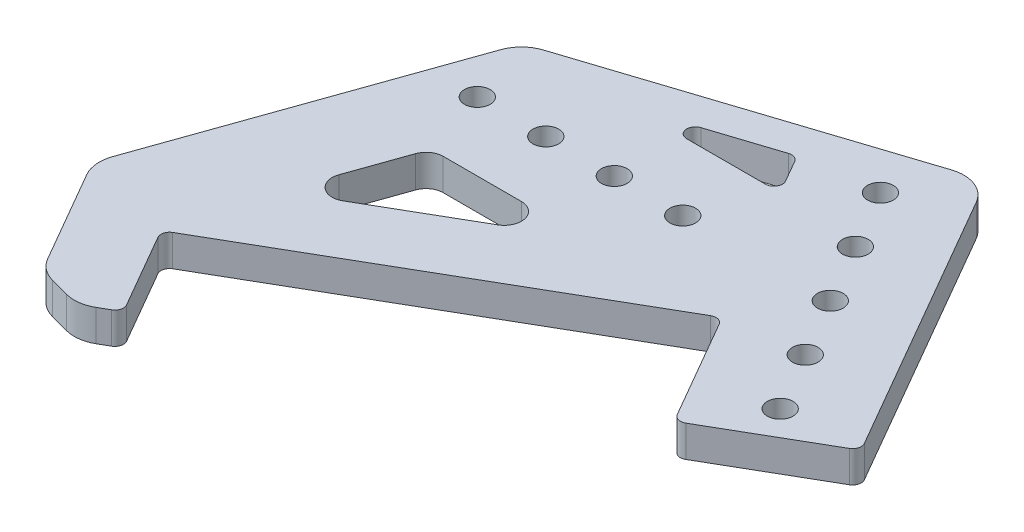
SolidWorks part; units mm, degrees
ref_plane "Front Plane" through (0, 0, 0) normal (0, 0, 1) x (1, 0, 0)
ref_plane "Top Plane" through (0, 0, 0) normal (0, 1, 0) x (1, 0, 0)
ref_plane "Right Plane" through (0, 0, 0) normal (1, 0, 0) x (0, 0, -1)
sketch "Sketch1" plane through (0, 0, 0) normal (0, 1, 0) x (1, 0, 0)
  line L0 (0, 0) -> (-31.75, 54.9926) construction
  line L1 (-15.875, 27.4963) -> (-85.725, 27.4963) construction
  line L2 (-10.9985, -6.35) -> (-23.2073, 14.7963)
  line L3 (-10.9985, -6.35) -> (10.9985, 6.35)
  line L4 (-23.2073, 14.7963) -> (-89.1985, -23.3037)
  line L5 (10.9985, 6.35) -> (-20.7515, 61.3426)
  line L6 (-10.9985, -6.35) -> (-20.7515, 61.3426) construction
  line L7 (-42.7485, 48.6426) -> (10.9985, 6.35) construction
  line L8 (-37.872, 40.1963) -> (-42.1959, 47.6855)
  line L9 (-65.2068, 40.1963) -> (-37.872, 40.1963)
  line L12 (-85.725, 40.1963) -> (-20.7515, 61.3426)
  line L13 (-65.2068, 40.1963) -> (-42.1959, 47.6855)
  line L14 (-89.1985, -23.3037) -> (-82.8485, -34.3022)
  line L16 (-83.7598, 34.1581) -> (-18.7863, 55.3044) construction
  line L17 (-106.547, -18.6552) -> (-93.847, -40.6522)
  line L18 (-106.547, -18.6552) -> (-85.725, 40.1963)
  line L19 (-29.5573, 25.7948) -> (-106.547, -18.6552) construction
  line L20 (-82.8485, -34.3022) -> (-79.6735, -39.8015)
  line L21 (-79.6735, -39.8015) -> (-85.1727, -42.9765)
  line L22 (-85.1727, -42.9765) -> (-93.847, -40.6522)
  circle A0 centre (-28.575, 49.4934) radius 2.3813
  circle A1 centre (-22.225, 38.4948) radius 2.3813
  circle A2 centre (-15.875, 27.4963) radius 2.3813
  circle A3 centre (-9.525, 16.4978) radius 2.3813
  circle A4 centre (-3.175, 5.4993) radius 2.3813
  circle A5 centre (-43.2397, 27.4963) radius 2.3812
  circle A6 centre (-55.9397, 27.4963) radius 2.3813
  circle A7 centre (-68.6397, 27.4963) radius 2.3813
  circle A8 centre (-81.3397, 27.4963) radius 2.3812
  point P30 (-85.725, 27.4963)
  dimension "D3" = 4.7625
  dimension "D6" = 4.7625
  dimension "D1" = 63.5
  dimension "D2" = 69.85
  dimension "D4" = 6.35
  dimension "D7" = 27.3647
  dimension "D9" = 25.4
  dimension "D10" = 60
  dimension "D12" = 6.35
  dimension "D13" = 76.2
  dimension "D14" = 12.7
  dimension "D16" = 19.05
  dimension "D17" = 6.35
  dimension "D15" = 12.7
  dimension "D5" = 5
  dimension "D8" = 4
extrude "Boss-Extrude1" add sketch "Sketch1" along normal blind 5.842
fillet "Fillet1" radius 1.5875 3 edges at (-37.872, 2.921, -40.1963) (-65.2068, 2.921, -40.1963) (-42.1959, 2.921, -47.6855)
fillet "Fillet2" radius 6.35 5 edges at (-85.725, 2.921, -40.1963) (-20.7515, 2.921, -61.3426) (-85.1727, 2.921, 42.9765) (-93.847, 2.921, 40.6522) (-106.547, 2.921, 18.6552)
fillet "Fillet3" radius 1.5875 5 edges at (-79.6735, 2.921, 39.8015) (-89.1985, 2.921, 23.3037) (-23.2073, 2.921, -14.7963) (10.9985, 2.921, -6.35) (-10.9985, 2.921, 6.35)
sketch "Sketch2" plane through (0, 5.842, 0) normal (0, 1, 0) x (1, 0, 0)
  line L0 (-84.55, -5.9552) -> (-48.6073, 14.7963)
  line L1 (-87.8237, -22.5099) -> (-24.5822, 14.0026) construction
  line L2 (-56.2029, -4.2537) -> (-62.5529, 6.7448) construction
  line L3 (-48.6073, 14.7963) -> (-77.208, 14.7963)
  line L4 (-84.55, -5.9552) -> (-77.208, 14.7963)
  line L5 (-43.2397, 27.4963) -> (-81.3397, 27.4963) construction
  line L6 (-86.7692, 37.2449) -> (-105.5709, -15.8964) construction
  dimension "D2" = 12.7
  dimension "D3" = 12.7
extrude "Cut-Extrude1" cut sketch "Sketch2" against normal through all
fillet "Fillet4" radius 3.175 3 edges at (-48.6073, 2.921, -14.7963) (-84.55, 2.921, 5.9552) (-77.208, 2.921, -14.7963)
